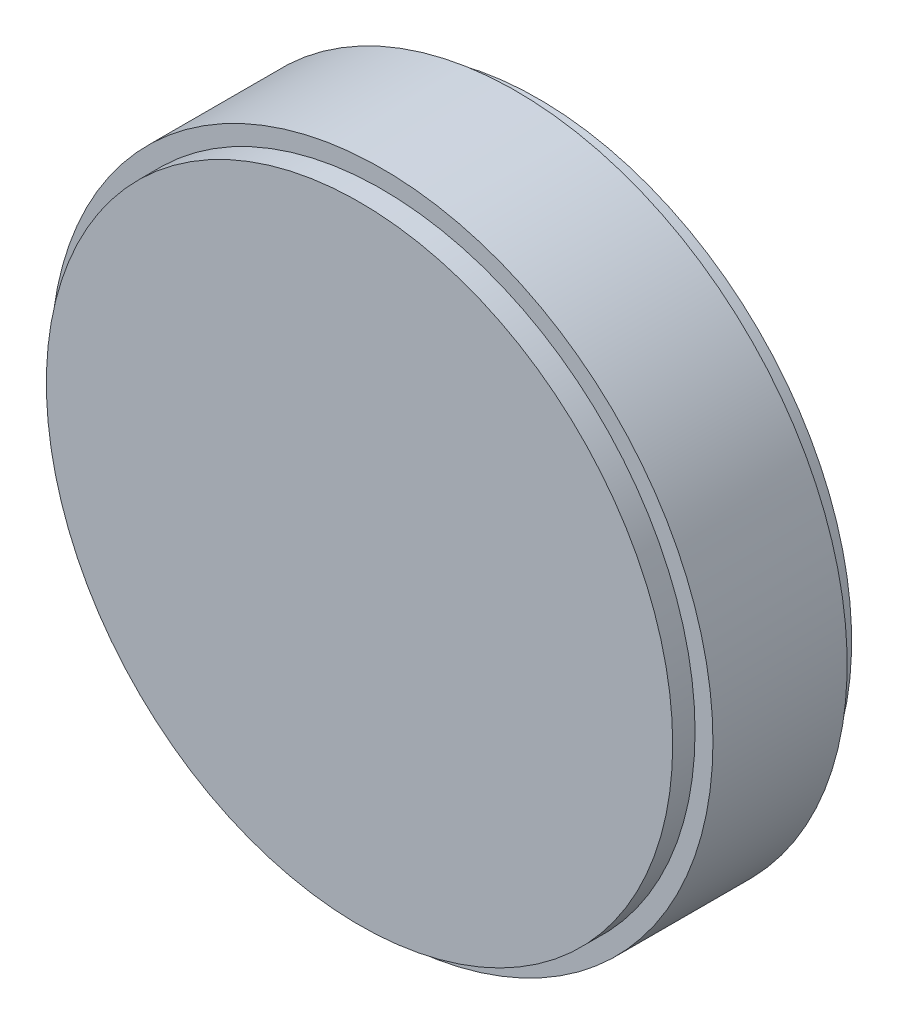
SolidWorks part; units mm, degrees
ref_plane "Front Plane" through (0, 0, 0) normal (0, 0, 1) x (1, 0, 0)
ref_plane "Top Plane" through (0, 0, 0) normal (0, 1, 0) x (1, 0, 0)
ref_plane "Right Plane" through (0, 0, 0) normal (1, 0, 0) x (0, 0, -1)
sketch "Sketch1" plane through (0, 0, 0) normal (0, 0, 1) x (1, 0, 0)
  circle A0 centre (0, 0) radius 74
  dimension "D1" = 148
extrude "Boss-Extrude1" add sketch "Sketch1" along normal mid plane 40
sketch "Sketch2" plane through (0, 0, 20) normal (0, 0, 1) x (1, 0, 0)
  circle A0 centre (0, 0) radius 70
  circle M2 centre (0, 0) radius 74
  dimension "D1" = 140
extrude "Cut-Extrude1" cut sketch "Sketch2" against normal blind 5 contours A0 M2
sketch "Sketch3" plane through (0, 0, -20) normal (0, 0, -1) x (-1, 0, 0)
  circle A0 centre (0, 0) radius 70
  circle M2 centre (0, 0) radius 74
  dimension "D1" = 140
extrude "Cut-Extrude2" cut sketch "Sketch3" against normal blind 5 contours A0 M2
